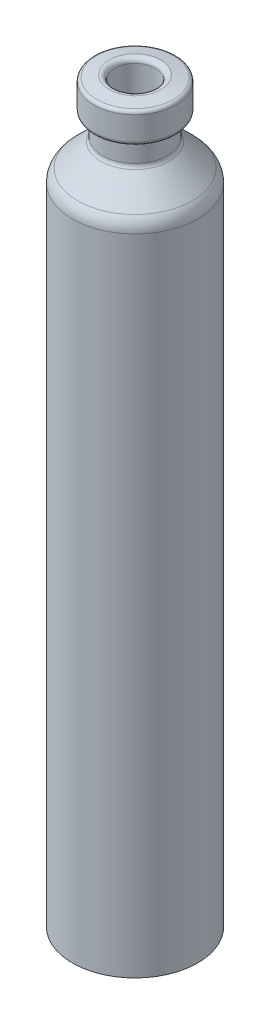
SolidWorks part; units mm, degrees
ref_plane "Front Plane" through (0, 0, 0) normal (0, 0, 1) x (1, 0, 0)
ref_plane "Top Plane" through (0, 0, 0) normal (0, 1, 0) x (1, 0, 0)
ref_plane "Right Plane" through (0, 0, 0) normal (1, 0, 0) x (0, 0, -1)
sketch "Sketch2" plane through (0, 0, 0) normal (1, 0, 0) x (0, 0, -1)
  line L0 (-5.475, 0) -> (-5.475, 17.4824) construction
  dimension "D1" = 5.475
ref_axis "Axis1" through (0, 0, 5.475) along (0, 1, 0)
sketch "Sketch1" plane through (0, 0, 0) normal (1, 0, 0) x (0, 0, -1)
  line L0 (0, 0) -> (0, 56.2828)
  line L1 (-0.85, 0) -> (-0.85, 55.7172)
  line L2 (-0.4741, 57.4195) -> (-2.4769, 59.4033)
  line L3 (-1.3241, 56.8539) -> (-3.5519, 59.0605)
  line L4 (-0.85, 0) -> (0, 0)
  line L5 (-3.7, 59.4158) -> (-3.7, 64.0648)
  line L6 (-3.2237, 64.4574) -> (-2.1428, 64.2473)
  line L7 (-1.9, 63.9528) -> (-1.9, 61.8802)
  line L8 (-2.625, 59.7585) -> (-2.625, 61.2255)
  line L9 (-2.4026, 61.5153) -> (-2.1224, 61.5904)
  line L10 (-5.475, 0) -> (-5.475, 17.4824) construction
  arc A0 (-0.85, 55.7172) -> (-1.3241, 56.8539) centre (-2.45, 55.7172) ccw
  arc A1 (0, 56.2828) -> (-0.4741, 57.4195) centre (-1.6, 56.2828) ccw
  arc A2 (-2.4769, 59.4033) -> (-2.625, 59.7585) centre (-2.125, 59.7585) cw
  arc A3 (-3.5519, 59.0605) -> (-3.7, 59.4158) centre (-3.2, 59.4158) cw
  arc A4 (-2.1428, 64.2473) -> (-1.9, 63.9528) centre (-2.2, 63.9528) cw
  arc A5 (-2.1224, 61.5904) -> (-1.9, 61.8802) centre (-2.2, 61.8802) ccw
  arc A6 (-2.625, 61.2255) -> (-2.4026, 61.5153) centre (-2.325, 61.2255) cw
  arc A7 (-3.7, 64.0648) -> (-3.2237, 64.4574) centre (-3.3, 64.0648) cw
  point P19 (0, 56.95)
  point P22 (-2.625, 59.55)
  point P25 (-3.7, 59.2073)
  point P30 (-1.9, 61.65)
  point P35 (-3.7, 64.55)
  dimension "D12" = 1.6
  dimension "D13" = 0.5
  dimension "D14" = 0.3
  dimension "D15" = 0.4
  dimension "D1" = 56.95
  dimension "D2" = 0.85
  dimension "D3" = 2.625
  dimension "D4" = 64.55
  dimension "D5" = 79
  dimension "D6" = 5
  dimension "D7" = 1
  dimension "D9" = 1.9
  dimension "D10" = 105
  dimension "D8" = 2.1
  dimension "D11" = 1.775
revolve "Revolve1" add sketch "Sketch1" angle 360 about axis through (0, 0, 5.475) along (0, 1, 0)
equation "\"Height\"= 64.55"
equation "\"D1@Sketch1\"=\"Height\"-7.6"
equation "\"D3@Sketch1\"=10.95/2-5.7/2"
equation "\"D4@Sketch1\"=\"Height\""
equation "\"D5@Sketch1\"=90-11"
equation "\"D9@Sketch1\"=10.95/2-7.15/2"
equation "\"D10@Sketch1\"=90+15"
equation "\"D8@Sketch1\"=5-2.9"
equation "\"D1@Sketch2\"=10.95/2"
equation "\"D11@Sketch1\"=3.55/2"
